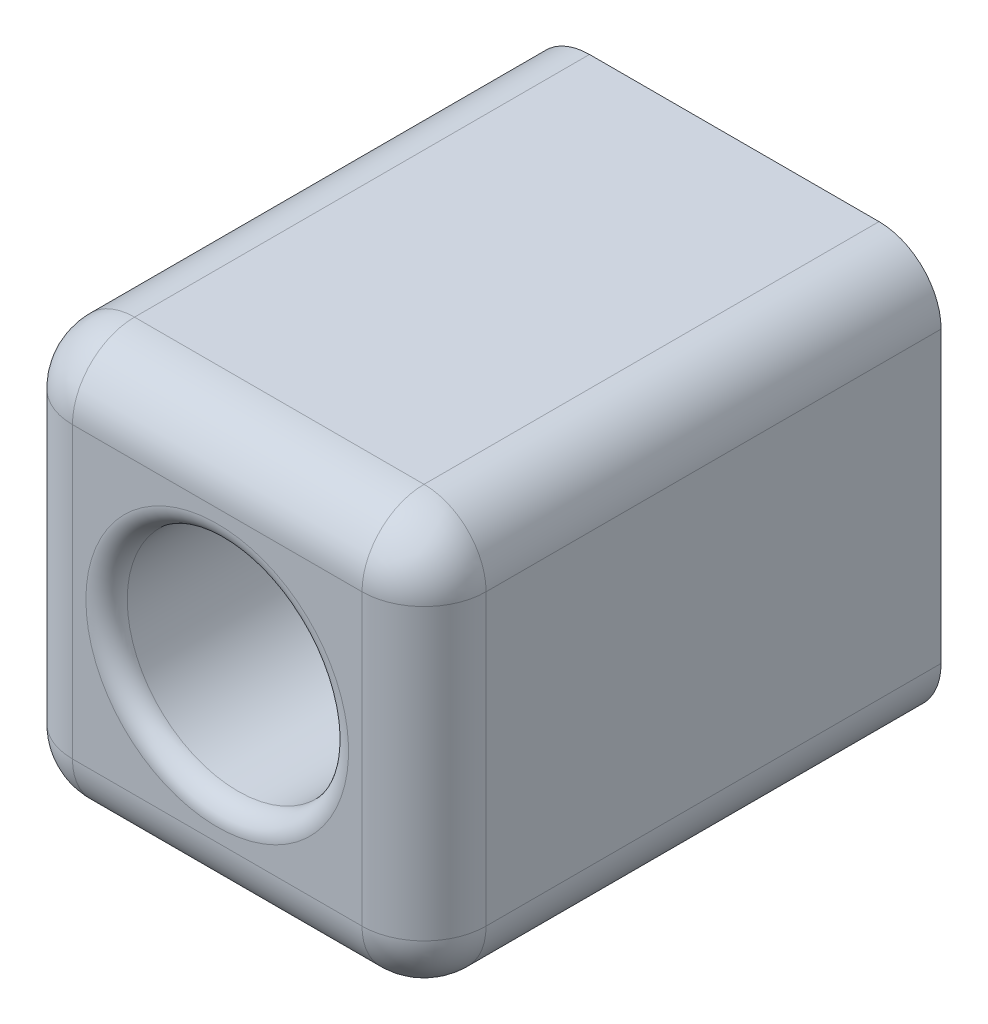
SolidWorks part; units mm, degrees
ref_plane "Front Plane" through (0, 0, 0) normal (0, 0, 1) x (1, 0, 0)
ref_plane "Top Plane" through (0, 0, 0) normal (0, 1, 0) x (1, 0, 0)
ref_plane "Right Plane" through (0, 0, 0) normal (1, 0, 0) x (0, 0, -1)
sketch "Sketch1" plane through (0, 0, 0) normal (0, 0, 1) x (1, 0, 0)
  line L1 (-7, -10) -> (7, -10)
  line L2 (-10, -7) -> (-10, 7)
  line L3 (-7, 10) -> (7, 10)
  line L4 (10, -7) -> (10, 7)
  line L5 (-10, -10) -> (10, 10) construction
  line L6 (-10, 10) -> (10, -10) construction
  arc A0 (10, -7) -> (7, -10) centre (7, -7) cw
  arc A1 (-10, -7) -> (-7, -10) centre (-7, -7) ccw
  arc A2 (-10, 7) -> (-7, 10) centre (-7, 7) cw
  arc A3 (7, 10) -> (10, 7) centre (7, 7) cw
  circle A4 centre (0, 0) radius 3.2
  point P0 (0, 0)
  dimension "D1" = 3
extrude "Boss-Extrude1" add sketch "Sketch1" along normal blind 25
fillet "Fillet1" radius 3 8 edges at (9.1213, -9.1213, 25) (0, -10, 25) (-9.1213, -9.1213, 25) (-10, 0, 25) (-9.1213, 9.1213, 25) (0, 10, 25) (9.1213, 9.1213, 25) (10, 0, 25)
sketch "Sketch2" plane through (0, 0, 25) normal (0, 0, 1) x (1, 0, 0)
  circle A0 centre (0, 0) radius 5.35
  dimension "D1" = 10.7
extrude "Cut-Extrude1" cut sketch "Sketch2" against normal offset from surface (19.5 mm away) 5.5 up to face at (0, 0, 0)
fillet "Fillet2" radius 1 1 edges at (5.35, 0, 25)
fillet "Fillet3" radius 1 1 edges at (-5.35, 0, 5.5)
